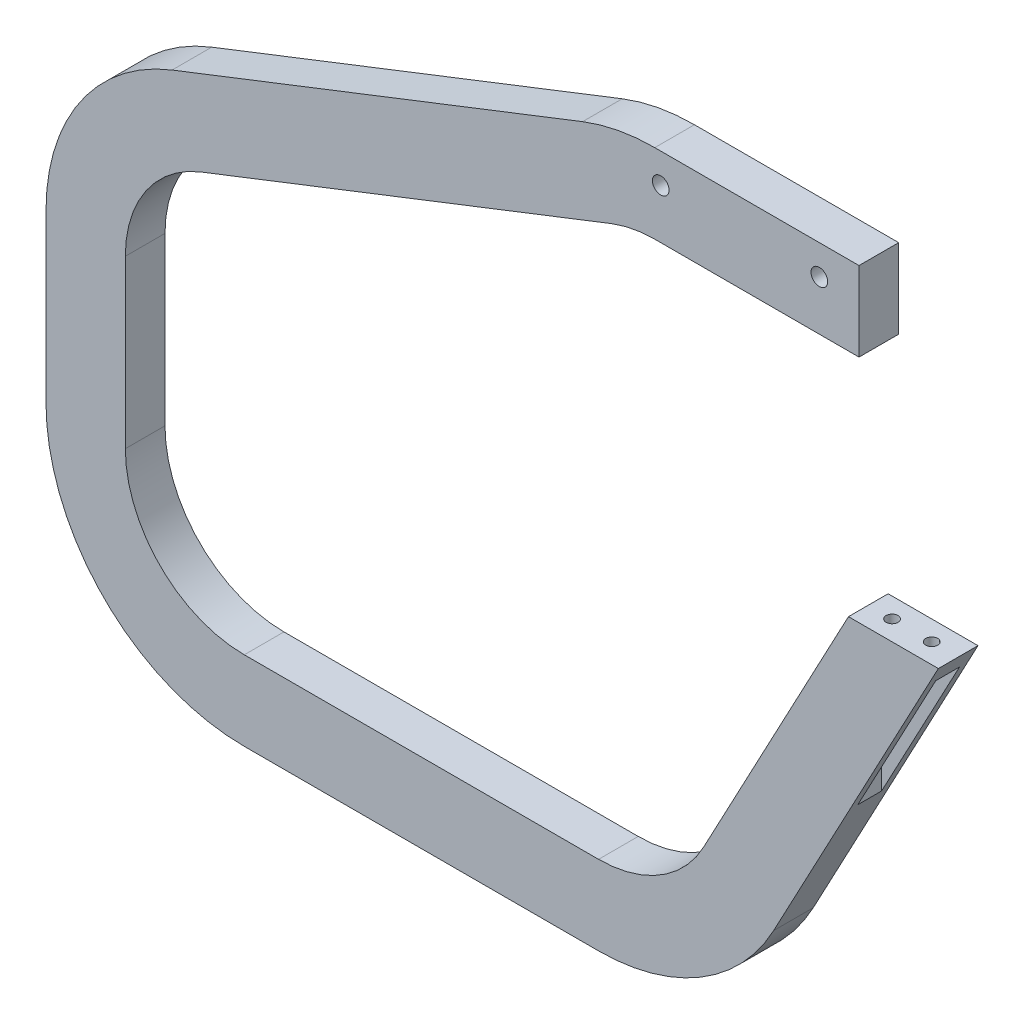
SolidWorks part; units mm, degrees
ref_plane "前视基准面" through (0, 0, 0) normal (0, 0, 1) x (1, 0, 0)
ref_plane "上视基准面" through (0, 0, 0) normal (0, 1, 0) x (1, 0, 0)
ref_plane "右视基准面" through (0, 0, 0) normal (1, 0, 0) x (0, 0, -1)
sketch "草图1" plane through (0, 0, 0) normal (0, 0, 1) x (1, 0, 0)
  line L0 (-137.9301, -127.3336) -> (-137.9301, 127.3336) construction
  line L1 (-176.9301, -127.3336) -> (-98.9301, -127.3336) construction
  line L2 (-98.9301, 127.3336) -> (-176.9301, 127.3336) construction
  line L3 (-225.1052, -135.4999) -> (-262.9301, -135.4999) construction
  line L5 (-232.9301, -77.4999) -> (-232.9301, -57.5)
  line L6 (-232.9301, -57.5) -> (-284.4239, -57.5)
  line L10 (-232.9301, -77.4999) -> (-284.4237, -77.4999)
  line L15 (-417.9301, -147.9799) -> (-417.9301, -190)
  line L16 (-387.9301, -240) -> (-298.6019, -240)
  line L18 (-387.9301, -220) -> (-298.6019, -220)
  line L22 (-212.9301, -135.4999) -> (-235.5893, -135.4999)
  line L24 (-345.3931, 0) -> (69.533, 0) construction
  line L25 (-345.3931, -39) -> (-345.3931, 39) construction
  line L26 (69.533, 39) -> (69.533, -39) construction
  line L27 (-212.9301, -135.4999) -> (-235.5893, -135.4999)
  line L28 (-302.6351, -60.9344) -> (-406.1413, -101.4144)
  line L29 (-295.3504, -79.5606) -> (-398.8568, -120.0406)
  line L30 (-235.5893, -135.4999) -> (-272.1226, -204.1014)
  line L31 (-337.9301, -77.4999) -> (-230.9301, -77.4999) construction
  line L32 (-254.4698, -213.5023) -> (-212.9301, -135.4999)
  line L33 (-437.9301, -147.9799) -> (-437.9301, -190)
  circle A0 centre (-242.9301, -65) radius 2.1 construction
  circle A1 centre (-282.9301, -65) radius 2.1 construction
  circle A2 centre (-242.9301, -65) radius 2.1
  circle A3 centre (-282.9301, -65) radius 2.1
  arc A4 (-298.6019, -220) -> (-272.1226, -204.1014) centre (-298.6019, -190) ccw
  arc A5 (-387.9301, -220) -> (-417.9301, -190) centre (-387.9301, -190) cw
  arc A6 (-417.9301, -147.9799) -> (-398.8568, -120.0406) centre (-387.9301, -147.9799) cw
  arc A7 (-284.4237, -77.4999) -> (-295.3504, -79.5606) centre (-284.4237, -107.4999) ccw
  arc A8 (-302.6351, -60.9344) -> (-284.4239, -57.5) centre (-284.4239, -107.5) cw
  arc A9 (-406.1413, -101.4144) -> (-437.9301, -147.9799) centre (-387.9301, -147.9799) ccw
  arc A10 (-437.9301, -190) -> (-387.9301, -240) centre (-387.9301, -190) ccw
  arc A11 (-298.6019, -240) -> (-254.4698, -213.5023) centre (-298.6019, -190) ccw
  point P39 (-280.5893, -220)
  point P47 (-417.9301, -127.4999)
  dimension "D1" = 20
  dimension "D2" = 10
  dimension "D3" = 7.5
  dimension "D11" = 30
  dimension "D13" = 50
  dimension "D14" = 50
  dimension "D15" = 50
  dimension "D16" = 50
  dimension "D4" = 20
  dimension "D5" = 240
  dimension "D6" = 20
  dimension "D7" = 300
  dimension "D8" = 20
  dimension "D9" = 20
  dimension "D10" = 50
  dimension "D12" = 45
extrude "凸台-拉伸1" add sketch "草图1" along normal blind 10 contours L16 A11 L32 L22 L30 A4 L18 A5 L15 A6 L29 A7 L10 L5 L6 A8 L28 A9 L33 A10 A2 A3
ref_plane "基准面2" through (0, 0, 5) normal (0, 0, 1) x (1, 0, 0)
sketch "草图4" plane through (0, 0, 5) normal (0, 0, 1) x (1, 0, 0)
  line L0 (-232.9301, -69) -> (-257.1849, -69)
  line L1 (-273.575, -72.091) -> (-404.3202, -123.2237)
  line L2 (-432.9301, -165.1328) -> (-432.9301, -189.7411)
  line L3 (-387.9301, -234.7411) -> (-299.096, -234.7411)
  line L4 (-259.3771, -210.8931) -> (-240.2397, -174.9575)
  line L5 (-230.5893, -140.4999) -> (-235.2397, -140.4999)
  line L6 (-235.2397, -140.4999) -> (-235.2397, -167.1528)
  line L7 (-240.2397, -174.9575) -> (-240.2397, -144.2324)
  line L9 (-230.5893, -140.4999) -> (-215.5928, -140.4999)
  line L10 (-235.2397, -140.4999) -> (-235.2397, -177.3925)
  line L12 (-387.9301, -240) -> (-298.6019, -240)
  line L13 (-254.4698, -213.5023) -> (-212.9301, -135.4999)
  line L14 (-212.9301, -135.4999) -> (-235.5893, -135.4999)
  line L15 (-235.5893, -135.4999) -> (-272.1226, -204.1014)
  line L16 (-298.6019, -220) -> (-387.9301, -220)
  line L17 (-417.9301, -190) -> (-417.9301, -147.9799)
  line L18 (-398.8568, -120.0406) -> (-295.3504, -79.5606)
  line L19 (-284.4237, -77.4999) -> (-232.9301, -77.4999)
  line L20 (-232.9301, -77.4999) -> (-232.9301, -57.5)
  line L21 (-232.9301, -57.5) -> (-284.4239, -57.5)
  line L22 (-302.6351, -60.9344) -> (-406.1413, -101.4144)
  line L23 (-437.9301, -147.9799) -> (-437.9301, -190)
  line L27 (-240.2397, -144.2324) -> (-272.1226, -204.1014)
  line L28 (-298.6019, -220) -> (-387.9301, -220)
  line L29 (-417.9301, -190) -> (-417.9301, -147.9799)
  line L30 (-398.8568, -120.0406) -> (-295.3504, -79.5606)
  line L31 (-284.4237, -77.4999) -> (-232.9301, -77.4999)
  line L32 (-232.9301, -77.4999) -> (-232.9301, -69)
  line L36 (-215.5928, -140.4999) -> (-235.2397, -177.3925)
  line L37 (-254.4698, -213.5023) -> (-212.9301, -135.4999) construction
  line L38 (-212.9301, -135.4999) -> (-235.5893, -135.4999) construction
  circle A0 centre (-242.9301, -65) radius 2.1 construction
  arc A1 (-299.096, -234.7411) -> (-259.3771, -210.8931) centre (-299.096, -189.7411) ccw
  arc A2 (-432.9301, -189.7411) -> (-387.9301, -234.7411) centre (-387.9301, -189.7411) ccw
  arc A3 (-404.3202, -123.2237) -> (-432.9301, -165.1328) centre (-387.9301, -165.1328) ccw
  arc A4 (-257.1849, -69) -> (-273.575, -72.091) centre (-257.1849, -114) ccw
  arc A8 (-298.6019, -240) -> (-254.4698, -213.5023) centre (-298.6019, -190) ccw
  arc A9 (-298.6019, -220) -> (-272.1226, -204.1014) centre (-298.6019, -190) ccw
  arc A10 (-417.9301, -190) -> (-387.9301, -220) centre (-387.9301, -190) ccw
  arc A11 (-398.8568, -120.0406) -> (-417.9301, -147.9799) centre (-387.9301, -147.9799) ccw
  arc A12 (-284.4237, -77.4999) -> (-295.3504, -79.5606) centre (-284.4237, -107.4999) ccw
  arc A13 (-284.4239, -57.5) -> (-302.6351, -60.9344) centre (-284.4239, -107.5) ccw
  arc A14 (-406.1413, -101.4144) -> (-437.9301, -147.9799) centre (-387.9301, -147.9799) ccw
  arc A15 (-437.9301, -190) -> (-387.9301, -240) centre (-387.9301, -190) ccw
  arc A17 (-298.6019, -220) -> (-272.1226, -204.1014) centre (-298.6019, -190) ccw
  arc A18 (-417.9301, -190) -> (-387.9301, -220) centre (-387.9301, -190) ccw
  arc A19 (-398.8568, -120.0406) -> (-417.9301, -147.9799) centre (-387.9301, -147.9799) ccw
  arc A20 (-284.4237, -77.4999) -> (-295.3504, -79.5606) centre (-284.4237, -107.4999) ccw
  dimension "D7" = 45
  dimension "D2" = 5
  dimension "D3" = 5
  dimension "D6" = 4
  dimension "D1" = 0
extrude "切除-拉伸1" cut sketch "草图4" against normal blind 3 and the other way blind 3 contours L9 L36 L10 L5 | L27 A17 L28 A18 L29 A19 L30 A20 L31 L32 L0 A4 L1 A3 L2 A2 L3 A1 L4 L7
sketch "草图5" plane through (0, -140.4999, 0) normal (0, -1, 0) x (1, 0, 0)
  line L0 (100.375, 5) -> (-100.375, 5) construction
  line L1 (-215.5928, 8) -> (-215.5928, 2) construction
  circle A0 centre (-229.5928, 5) radius 1.5
  circle A1 centre (-219.5928, 5) radius 1.5
  dimension "D1" = 3
  dimension "D2" = 3
  dimension "D3" = 4
  dimension "D4" = 10
extrude "切除-拉伸2" cut sketch "草图5" against normal blind 5
